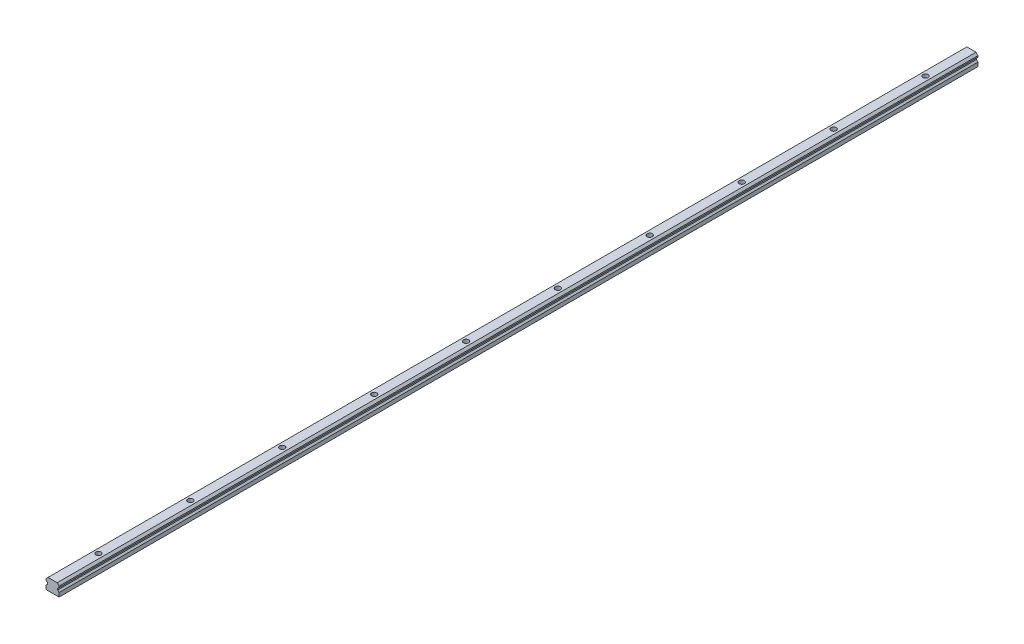
SolidWorks part; units mm, degrees
material "1023 Carbon Steel Sheet (SS)"
ref_plane "Front" through (0, 0, 0) normal (0, 0, 1) x (1, 0, 0)
ref_plane "Top" through (0, 0, 0) normal (0, 1, 0) x (1, 0, 0)
ref_plane "Right" through (0, 0, 0) normal (1, 0, 0) x (0, 0, -1)
sketch "Sketch1" plane through (0, 0, 0) normal (0, 0, 1) x (1, 0, 0)
  line L0 (0, 0) -> (0, 17.5)
  line L1 (7, 17.5) -> (-7, 17.5)
  line L2 (-7, 17.5) -> (-10, 14.5)
  line L3 (-10, 14.5) -> (-10, 12.5)
  line L4 (-10, 12.5) -> (-7.75, 10.25)
  line L5 (-7.75, 10.25) -> (-7.75, 8.25)
  line L6 (-7.75, 8.25) -> (-10, 6)
  line L7 (-10, 6) -> (-10, 0)
  line L8 (-10, 0) -> (10, 0)
  line L9 (10, 6) -> (10, 0)
  line L10 (7.75, 8.25) -> (10, 6)
  line L11 (7.75, 10.25) -> (7.75, 8.25)
  line L12 (10, 12.5) -> (7.75, 10.25)
  line L13 (10, 14.5) -> (10, 12.5)
  line L14 (7, 17.5) -> (10, 14.5)
  dimension "D1" = 17.5
  dimension "D2" = 10
  dimension "D3" = 10
  dimension "D4" = 135
  dimension "D5" = 2
  dimension "D6" = 2
  dimension "D7" = 7
  dimension "D8" = 6
extrude "Boss-Extrude1" add sketch "Sketch1" along normal blind 1400 contours L7 L8 L0 L1 L2 L3 L4 L5 L6 | L14 L1 L0 L8 L9 L10 L11 L12 L13
sketch "Sketch2" plane through (0, 17.5, 0) normal (0, 1, 0) x (1, 0, 0)
  line L0 (7, 0) -> (-7, 0) construction
  line L1 (7, -1400) -> (-7, -1400) construction
  circle A0 centre (0, -70) radius 4
  circle A1 centre (0, -210) radius 4
  circle A2 centre (0, -350) radius 4
  circle A3 centre (0, -490) radius 4
  circle A4 centre (0, -630) radius 4
  circle A5 centre (0, -770) radius 4
  circle A6 centre (0, -910) radius 4
  circle A7 centre (0, -1050) radius 4
  circle A8 centre (0, -1190) radius 4
  circle A9 centre (0, -1330) radius 4
  dimension "D1" = 8
  dimension "D3" = 70
  dimension "D4" = 70
  dimension "D2" = 10
extrude "Cut-Extrude1" cut sketch "Sketch2" against normal blind 26
